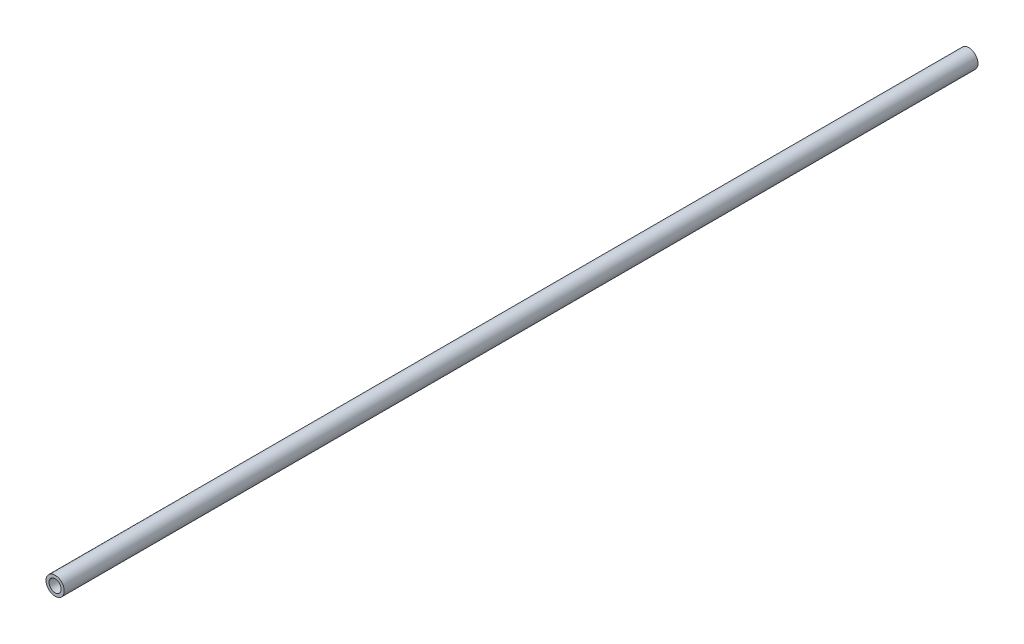
SolidWorks part; units mm, degrees
ref_plane "Ebene vorne" through (0, 0, 0) normal (0, 0, 1) x (1, 0, 0)
ref_plane "Ebene oben" through (0, 0, 0) normal (0, 1, 0) x (1, 0, 0)
ref_plane "Ebene rechts" through (0, 0, 0) normal (1, 0, 0) x (0, 0, -1)
sketch "Skizze1" plane through (0, 0, 0) normal (0, 0, 1) x (1, 0, 0)
  circle A0 centre (0, 0) radius 3
  circle A1 centre (0, 0) radius 2
  dimension "D1" = 6
  dimension "D2" = 4
extrude "Aufsatz-Linear austragen1" add sketch "Skizze1" along normal blind 300
